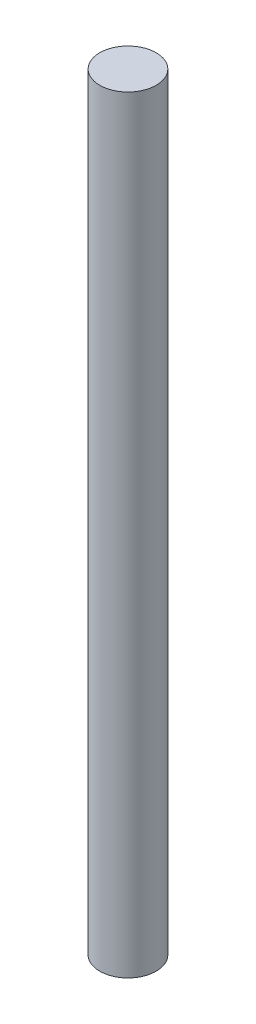
SolidWorks part; units mm, degrees
ref_plane "Front Plane" through (0, 0, 0) normal (0, 0, 1) x (1, 0, 0)
ref_plane "Top Plane" through (0, 0, 0) normal (0, 1, 0) x (1, 0, 0)
ref_plane "Right Plane" through (0, 0, 0) normal (1, 0, 0) x (0, 0, -1)
sketch "Sketch1" plane through (0, 0, 0) normal (0, 0, 1) x (1, 0, 0)
  line L5 (7.5, 204) -> (0, 204)
  line L6 (7.5, 204) -> (7.5, 0)
  line L7 (7.5, 0) -> (0, 0)
  line L8 (0, 204) -> (0, 0)
  line L9 (7.5, 204) -> (0, 0) construction
  line L10 (7.5, 0) -> (0, 204) construction
  point P0 (3.75, 102)
  dimension "D1" = 7.5
  dimension "D2" = 204
revolve "Revolve1" add sketch "Sketch1" angle 360 about L8
ref_plane "Plane1" through (0, 187, 0) normal (0, 1, 0) x (1, 0, 0)
sketch "Sketch2" plane through (0, 187, 0) normal (0, 1, 0) x (1, 0, 0)
  line L1 (1.5, 9) -> (-1.5, 9)
  line L2 (1.5, 9) -> (1.5, 6)
  line L3 (1.5, 6) -> (-1.5, 6)
  line L4 (-1.5, 9) -> (-1.5, 6)
  line L5 (1.5, 9) -> (-1.5, 6) construction
  line L6 (1.5, 6) -> (-1.5, 9) construction
  circle A0 centre (0, 0) radius 7.5 construction
  point P0 (0, 7.5)
  dimension "D1" = 3
extrude "Cut-Extrude1" cut sketch "Sketch2" against normal blind 18
ref_plane "Plane2" through (0, 104, 0) normal (0, -1, 0) x (-1, 0, 0)
sketch "Sketch3" plane through (0, 104, 0) normal (0, -1, 0) x (-1, 0, 0)
  line L1 (-1.5, 9) -> (1.5, 9)
  line L2 (-1.5, 9) -> (-1.5, 6)
  line L3 (-1.5, 6) -> (1.5, 6)
  line L4 (1.5, 9) -> (1.5, 6)
  line L5 (-1.5, 9) -> (1.5, 6) construction
  line L6 (-1.5, 6) -> (1.5, 9) construction
  circle A0 centre (0, 0) radius 7.5 construction
  point P0 (0, 7.5)
  point P7 (0, 0)
  dimension "D1" = 3
extrude "Cut-Extrude2" cut sketch "Sketch3" along normal blind 15
